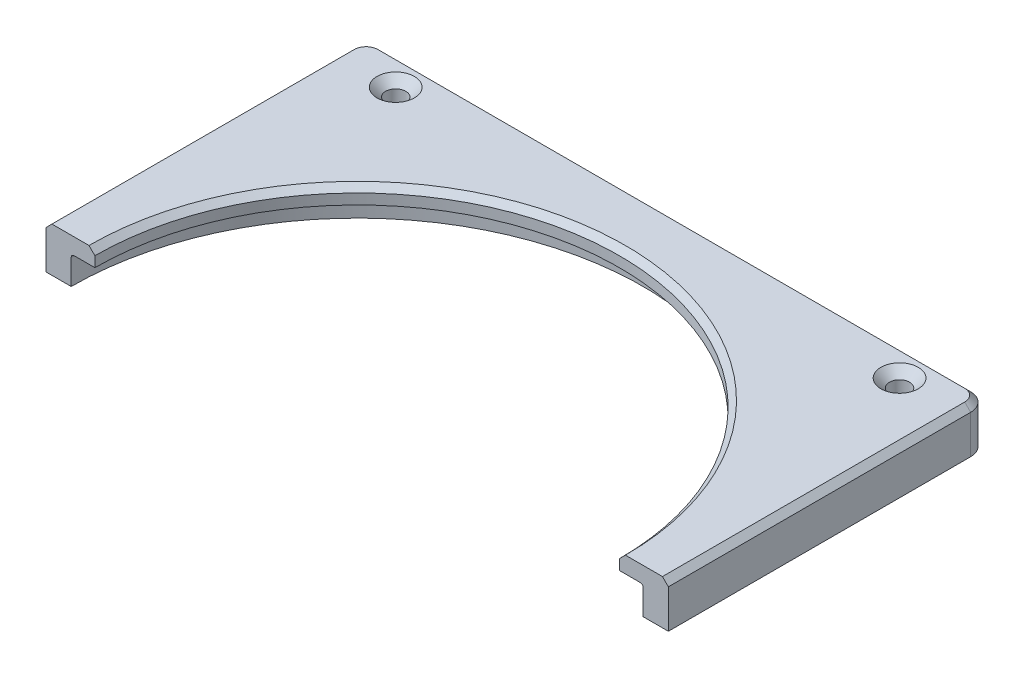
SolidWorks part; units mm, degrees
ref_plane "Front Plane" through (0, 0, 0) normal (0, 0, 1) x (1, 0, 0)
ref_plane "Top Plane" through (0, 0, 0) normal (0, 1, 0) x (1, 0, 0)
ref_plane "Right Plane" through (0, 0, 0) normal (1, 0, 0) x (0, 0, -1)
sketch "Sketch1" plane through (0, 0, 0) normal (0, 1, 0) x (1, 0, 0)
  line L1 (-52.5, 27) -> (52.5, 27)
  line L2 (-52.5, 27) -> (-52.5, -27)
  line L3 (-52.5, -27) -> (52.5, -27)
  line L4 (52.5, 27) -> (52.5, -27)
  line L5 (0, -27) -> (0, 27) construction
  line L6 (-52.5, 0) -> (52.5, 0) construction
  point P0 (0, 0)
  dimension "D1" = 105
  dimension "D2" = 54
extrude "Boss-Extrude2" add sketch "Sketch1" along normal blind 7.5
sketch "Sketch2" plane through (0, 0, 0) normal (0, -1, 0) x (1, 0, 0)
  line L0 (-52.5, 27) -> (52.5, 27) construction
  circle A0 centre (0, 27) radius 48.25
  dimension "D1" = 96.5
extrude "Cut-Extrude1" cut sketch "Sketch2" against normal blind 4.75
sketch "Sketch3" plane through (0, 7.5, 0) normal (0, 1, 0) x (1, 0, 0)
  line L0 (-52.5, -27) -> (52.5, -27) construction
  circle A0 centre (0, -27) radius 44.25
  dimension "D1" = 88.5
extrude "Cut-Extrude2" cut sketch "Sketch3" against normal through all
sketch "Sketch4" plane through (0, 7.5, 0) normal (0, 1, 0) x (1, 0, 0)
  line L0 (0, 27) -> (0, 22) construction
  line L1 (52.5, 27) -> (-52.5, 27) construction
  line L3 (-42.5, 22) -> (42.5, 22) construction
  point P0 (-42.5, 22)
  point P2 (42.5, 22)
  dimension "D1" = 85
  dimension "D2" = 5
hole_wizard "CSK for M3 Flat Head Machine Screw1" positions "Sketch4" profile "Sketch5" countersink size "M3" standard "ANSI Metric" end condition through all
sketch "Sketch5" plane through (-42.5, 7.5, -22) normal (1, 0, 0) x (0, 0, 1)
  line L0 (0, 0) -> (0, 7.5)
  line L1 (0, 7.5) -> (2.2, 7.5)
  line L2 (1.7, 7) -> (1.7, 1.45)
  line L3 (1.7, 1.45) -> (3.15, 0)
  line L5 (3.15, 0) -> (0, 0)
  line L6 (-1.7, 1.45) -> (-3.15, 0) construction
  line L7 (2.2, 7.5) -> (1.7, 7)
  line L8 (-2.2, 7.5) -> (-1.7, 7) construction
  line L11 (0, -6.35) -> (0, 107.95) construction
  dimension "Thru Hole Dia." = 3.4
  dimension "Thru Hole Depth" = 7.5
  dimension "Near C'Sink Dia." = 6.3
  dimension "Near C'Sink Angle" = 90
  dimension "Far C'Sink Dia." = 4.4
  dimension "Far C'Sink Angle" = 90
fillet "Fillet1" radius 3 2 edges at (-52.5, 3.75, -27) (52.5, 3.75, -27)
chamfer "Chamfer1" distance 1 angle 45 6 edges at (0, 7.5, -17.25) (-52.5, 7.5, 1.5) (-51.6213, 7.5, -26.1213) (0, 7.5, -27) (51.6213, 7.5, -26.1213) (52.5, 7.5, 1.5)
fillet "Fillet2" radius 0.5 1 edges at (0, 4.75, -21.25)
